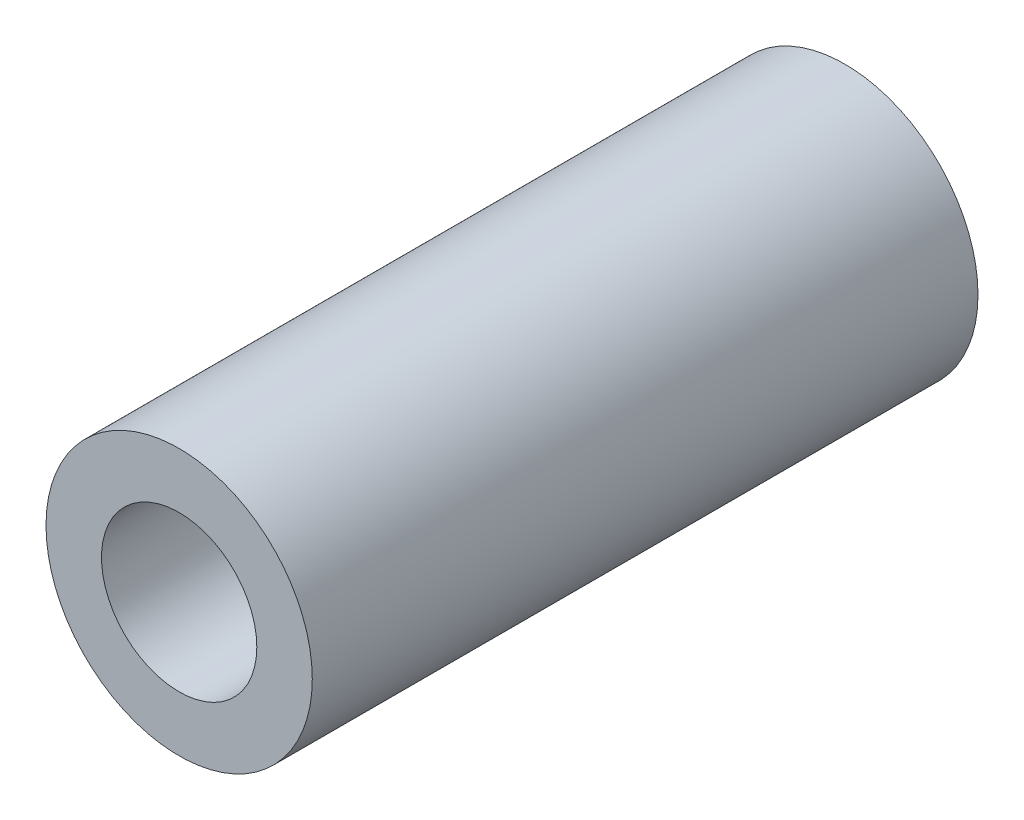
SolidWorks part; units mm, degrees
ref_plane "Front Plane" through (0, 0, 0) normal (0, 0, 1) x (1, 0, 0)
ref_plane "Top Plane" through (0, 0, 0) normal (0, 1, 0) x (1, 0, 0)
ref_plane "Right Plane" through (0, 0, 0) normal (1, 0, 0) x (0, 0, -1)
sketch "Sketch1" plane through (0, 0, 0) normal (0, 0, 1) x (1, 0, 0)
  circle A0 centre (0, 0) radius 3
  circle A1 centre (0, 0) radius 1.75
  dimension "D1" = 3.5
  dimension "D2" = 6
extrude "Boss-Extrude1" add sketch "Sketch1" along normal blind 15
